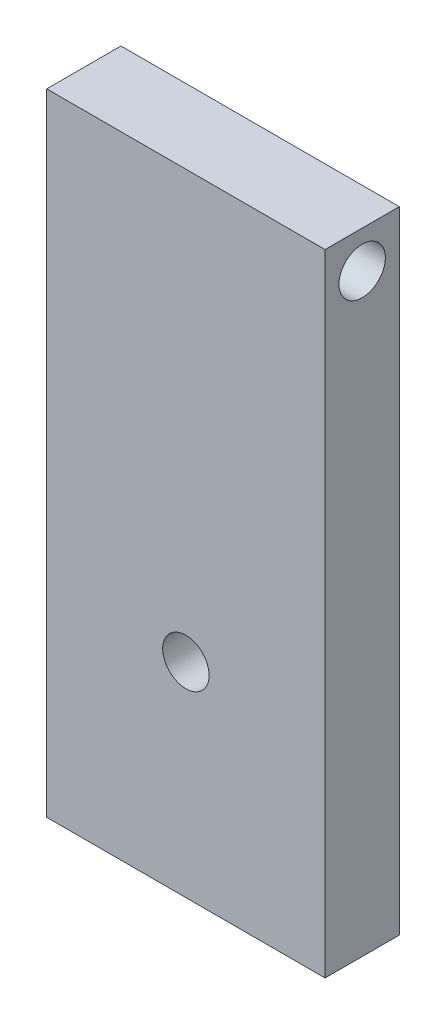
SolidWorks part; units mm, degrees
ref_plane "Alzado" through (0, 0, 0) normal (0, 0, 1) x (1, 0, 0)
ref_plane "Planta" through (0, 0, 0) normal (0, 1, 0) x (1, 0, 0)
ref_plane "Vista lateral" through (0, 0, 0) normal (1, 0, 0) x (0, 0, -1)
sketch "Croquis1" plane through (0, 0, 0) normal (0, 0, 1) x (1, 0, 0)
  line L1 (-15, 34) -> (15, 34)
  line L2 (-15, 34) -> (-15, -34)
  line L3 (-15, -34) -> (15, -34)
  line L4 (15, 34) -> (15, -34)
  line L5 (-15, 34) -> (15, -34) construction
  line L6 (-15, -34) -> (15, 34) construction
  point P0 (0, 0)
  dimension "D1" = 30
  dimension "D2" = 68
extrude "Saliente-Extruir1" add sketch "Croquis1" against normal blind 8
sketch "Croquis2" plane through (15, 0, 0) normal (1, 0, 0) x (0, 0, -1)
  line L0 (8, 34) -> (0, 34) construction
  line L1 (0, -34) -> (0, 34) construction
  circle A0 centre (4, 30) radius 2.5
  dimension "D2" = 4
  dimension "D3" = 5
  dimension "D1" = 4
extrude "Cortar-Extruir1" cut sketch "Croquis2" against normal through all
sketch "Croquis3" plane through (0, -34, 0) normal (0, -1, 0) x (1, 0, 0)
  line L0 (-15, 0) -> (15, 0) construction
  circle A0 centre (-10, -4) radius 2
  circle A1 centre (10, -4) radius 2
  dimension "D3" = 4
  dimension "D4" = 4
  dimension "D5" = 4
  dimension "D6" = 4
  dimension "D1" = 10
  dimension "D2" = 10
extrude "Cortar-Extruir2" cut sketch "Croquis3" against normal blind 15
sketch "Croquis4" plane through (0, 0, 0) normal (0, 0, 1) x (1, 0, 0)
  line L0 (-15, 34) -> (-15, -34) construction
  line L1 (15, 34) -> (-15, 34) construction
  circle A0 centre (0, -12) radius 2.5
  dimension "D1" = 15
  dimension "D2" = 46
  dimension "D3" = 5
extrude "Cortar-Extruir3" cut sketch "Croquis4" against normal through all
